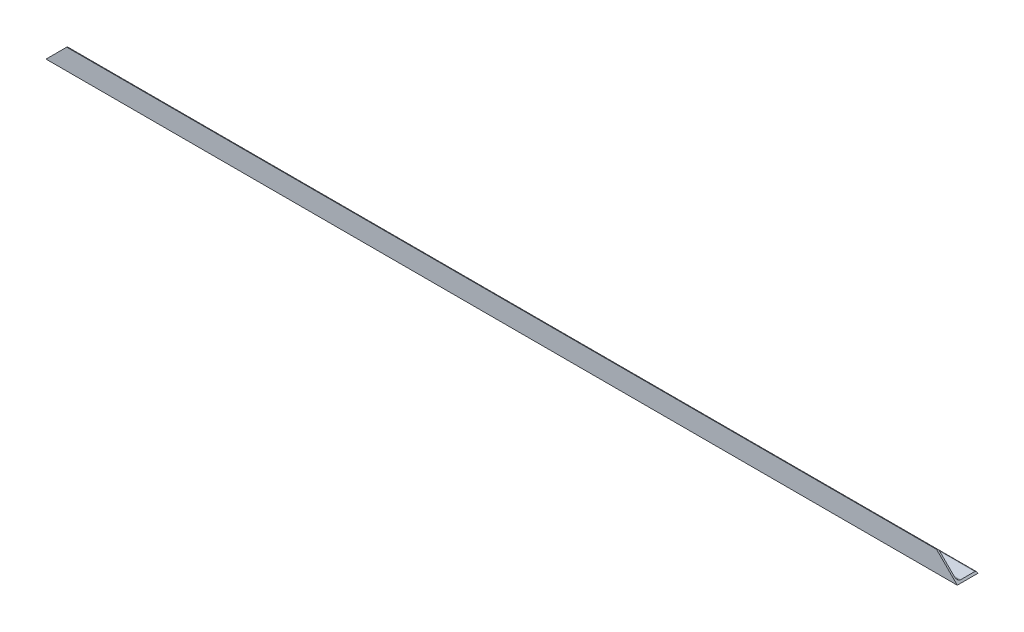
SolidWorks part; units mm, degrees
ref_plane "Front Plane" through (0, 0, 0) normal (0, 0, 1) x (1, 0, 0)
ref_plane "Top Plane" through (0, 0, 0) normal (0, 1, 0) x (1, 0, 0)
ref_plane "Right Plane" through (0, 0, 0) normal (1, 0, 0) x (0, 0, -1)
sketch "Sketch1" plane through (0, 0, 0) normal (0, 1, 0) x (1, 0, 0)
  line L0 (0, 0) -> (1760, 0)
  dimension "D1" = 1760
other "L angle (equal) 40X40X3(7)"
ref_plane "Plane1" through (0, 0, 0) normal (1, 0, 0) x (0, 0, -1)
sketch "Sketch13" plane through (0, 0, 0) normal (1, 0, 0) x (0, 0, -1)
  line L0 (0, 40) -> (0, 0)
  line L2 (3, 37) -> (3, 9)
  line L3 (9, 3) -> (37, 3)
  line L5 (40, 0) -> (0, 0)
  arc A0 (3, 37) -> (0, 40) centre (0, 37) ccw
  arc A1 (40, 0) -> (37, 3) centre (37, 0) ccw
  arc A2 (9, 3) -> (3, 9) centre (9, 9) cw
  point P8 (0, 20)
  point P9 (20, 0)
  point P10 (0, 0)
  dimension "Radius_2" = 3
  dimension "Radius_1" = 6
  dimension "V_leg" = 40
  dimension "H_leg" = 40
  dimension "thickness" = 3
sketch "Sketch14" plane through (0, 0, 0) normal (0, 0, 1) x (1, 0, 0)
  line L0 (1760, 0) -> (1760, 40)
  line L1 (0, 40) -> (0, 0)
  line L2 (40, 40) -> (0, 0)
  line L3 (1720, 40) -> (1760, 0)
  line L4 (0, 40) -> (0, 0)
  line L5 (0, 0) -> (1760, 0)
  line L6 (1760, 0) -> (1760, 40)
  line L7 (1760, 40) -> (0, 40)
  line L8 (0, 40) -> (0, 0) construction
  line L10 (1760, 0) -> (1760, 40) construction
  line L11 (1760, 40) -> (1720, 40)
  line L12 (40, 40) -> (0, 40)
  line L13 (40, 40) -> (1720, 40) construction
  dimension "D2" = 40
  dimension "D1" = 0
extrude "Cut-Extrude1" cut sketch "Sketch14" against normal through all
